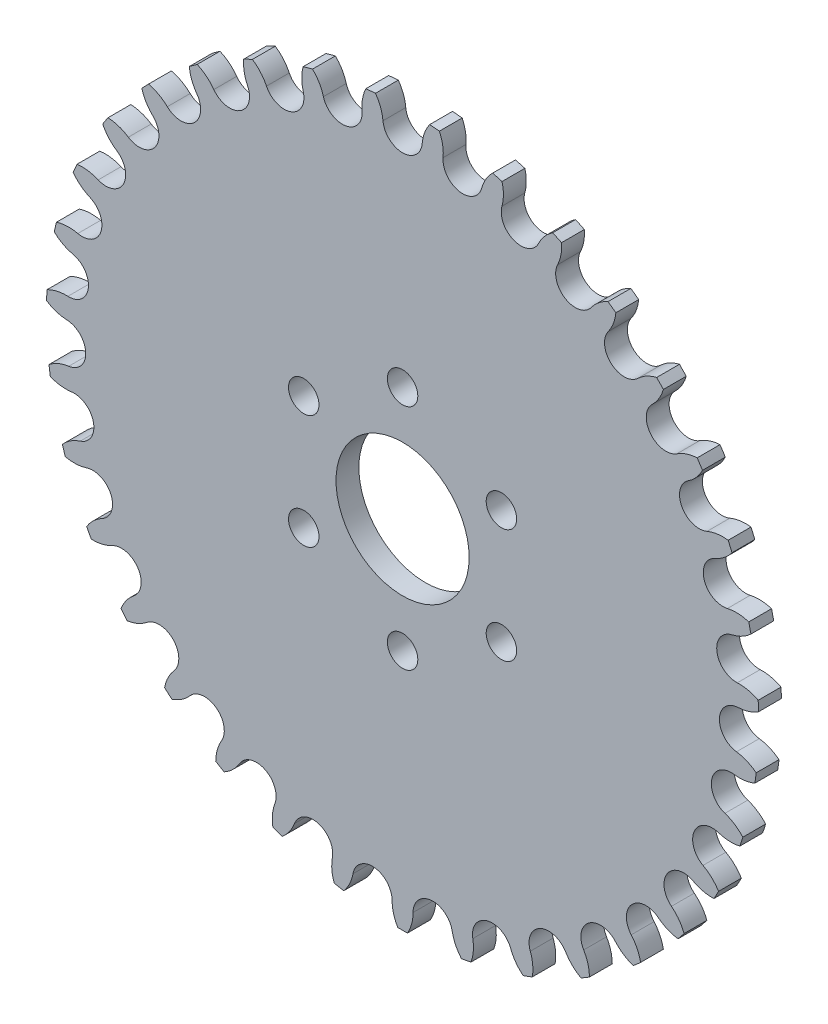
SolidWorks part; units mm, degrees
material "AISI 1020"
ref_plane "Спереди" through (0, 0, 0) normal (0, 0, 1) x (1, 0, 0)
ref_plane "Сверху" through (0, 0, 0) normal (0, 1, 0) x (1, 0, 0)
ref_plane "Справа" through (0, 0, 0) normal (1, 0, 0) x (0, 0, -1)
sketch "Эскиз1" plane through (0, 0, 0) normal (0, 0, 1) x (1, 0, 0)
  line L0 (0, 0) -> (0, 85) construction
  line L1 (0, 85) -> (15.8056, 83.5176) construction
  line L2 (15.8056, 83.5176) -> (0, 0) construction
  line L3 (15.8056, 83.5176) -> (49.3989, 83.5176)
  line L4 (0, 0) -> (0, 88.5493)
  line L5 (0, 88.5493) -> (15.8111, 87.1263)
  line L6 (15.8111, 87.1263) -> (0, 0)
  circle A0 centre (0, 0) radius 85 construction
  circle A1 centre (0, 88.5493) radius 5.08
  circle A2 centre (15.8111, 87.1263) radius 5.08
  dimension "D1" = 170
  dimension "D6" = 10.16
  dimension "D2" = 15.875
  dimension "D3" = 10.716
  dimension "D4" = 33.5932
  dimension "D5" = 10.286
sketch "Эскиз2" plane through (0, 0, 0) normal (0, 0, 1) x (1, 0, 0)
  line L0 (0, 0) -> (0, 83.3693)
  line L1 (0, 0) -> (14.8862, 82.0295)
  line L4 (15.8111, 87.1263) -> (0, 0) construction
  arc A0 (10.6519, 87.5906) -> (9.6648, 93.1292) centre (0, 88.5493) ccw
  arc A1 (0, 93.6293) -> (16.7182, 92.1247) centre (0, 0) cw construction
  circle A2 centre (0, 88.5493) radius 5.08 construction
  circle A3 centre (15.8111, 87.1263) radius 5.08 construction
  circle A4 centre (0, 0) radius 85 construction
  circle A5 centre (0, 88.5493) radius 5.18
  arc A6 (0, 83.3693) -> (5.1591, 88.085) centre (0, 88.5493) ccw
  arc A7 (7.1194, 93.3583) -> (5.1591, 88.085) centre (15.8111, 87.1263) ccw
  circle A8 centre (15.8111, 87.1263) radius 5.18
  arc A9 (10.6519, 87.5906) -> (14.8862, 82.0295) centre (15.8111, 87.1263) ccw
  arc A10 (7.1194, 93.3583) -> (9.6648, 93.1292) centre (0, 0) cw
  dimension "D1" = 0.1
  dimension "D2" = 0.1
extrude "Бобышка-Вытянуть1" add sketch "Эскиз2" along normal blind 6
pattern_circular "Круговой массив1" count 35 over 360 about axis through (0, 0, 0) along (0, 0, 1) of "Бобышка-Вытянуть1"
sketch "Эскиз3" plane through (0, 0, 6) normal (0, 0, 1) x (1, 0, 0)
  line L0 (0, 0) -> (0, 30) construction
  line L1 (0, 0) -> (25.9808, 15) construction
  circle A0 centre (0, 0) radius 17.5
  circle A1 centre (0, 0) radius 30 construction
  circle A2 centre (0, 30) radius 4
  circle A3 centre (25.9808, 15) radius 4
  circle A4 centre (25.9808, -15) radius 4
  circle A5 centre (0, -30) radius 4
  circle A6 centre (-25.9808, -15) radius 4
  circle A7 centre (-25.9808, 15) radius 4
  dimension "D1" = 35
  dimension "D2" = 60
  dimension "D3" = 8
  dimension "D5" = 60
  dimension "D6" = 30
  dimension "D4" = 6
extrude "Вырез-Вытянуть1" cut sketch "Эскиз3" against normal through all
equation "\"D4@Эскиз1\"=360/\"D3@Эскиз1\""
equation "\"D5@Эскиз1\"=360/35"
